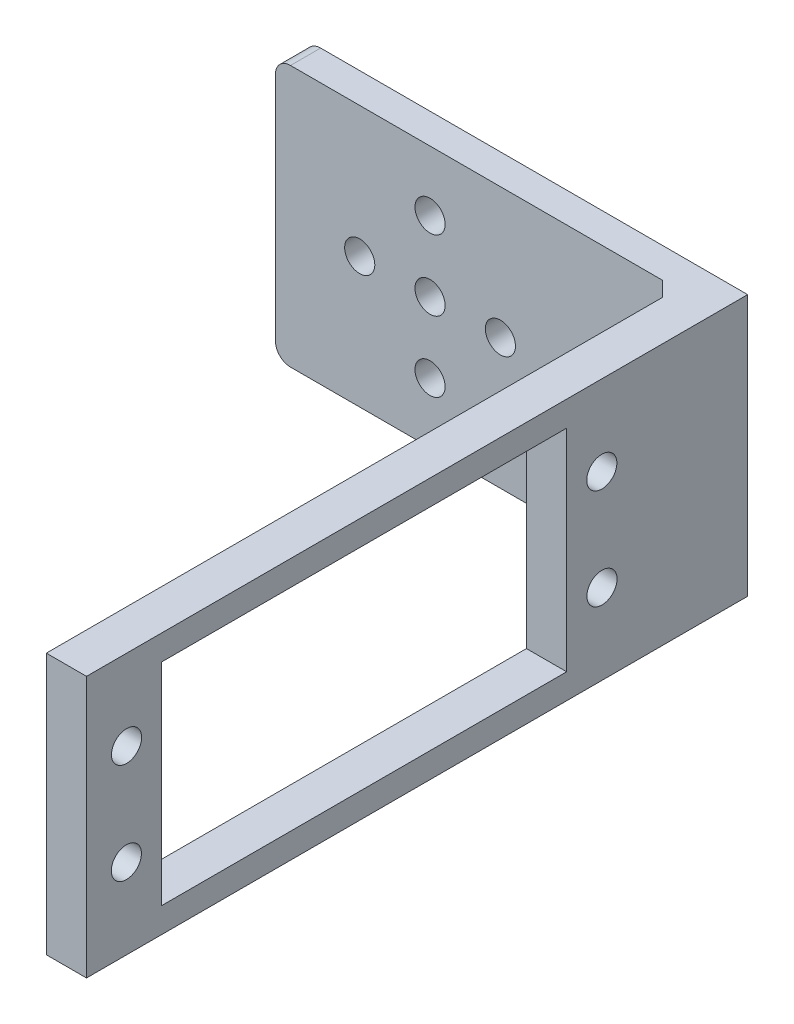
SolidWorks part; units mm, degrees
ref_plane "Alzado" through (0, 0, 0) normal (0, 0, 1) x (1, 0, 0)
ref_plane "Planta" through (0, 0, 0) normal (0, 1, 0) x (1, 0, 0)
ref_plane "Vista lateral" through (0, 0, 0) normal (1, 0, 0) x (0, 0, -1)
sketch "Croquis1" plane through (0, 0, 0) normal (0, 0, 1) x (1, 0, 0)
  line L0 (22, 0) -> (-6.61, 0) construction
  line L1 (-20.5, -13) -> (22, -13)
  line L2 (-22, -11.5) -> (-22, 11.5)
  line L3 (-20.5, 13) -> (22, 13)
  line L4 (22, -13) -> (22, 13)
  line L5 (-22, -13) -> (22, 13) construction
  line L6 (-22, 13) -> (22, -13) construction
  arc A0 (-20.5, -13) -> (-22, -11.5) centre (-20.5, -11.5) cw
  arc A1 (-22, 11.5) -> (-20.5, 13) centre (-20.5, 11.5) cw
  circle A2 centre (-6.61, 0) radius 1.5
  circle A3 centre (-13.61, 0) radius 1.5
  circle A4 centre (-6.61, 7) radius 1.5
  circle A5 centre (0.39, 0) radius 1.5
  circle A6 centre (-6.61, -7) radius 1.5
  point P0 (0, 0)
  dimension "D3" = 1.5
  dimension "D5" = 3
  dimension "D6" = 3
  dimension "D7" = 3
  dimension "D8" = 3
  dimension "D9" = 3
  dimension "D1" = 44
  dimension "D2" = 26
  dimension "D4" = 28.61
  dimension "D10" = 7
  dimension "D11" = 7
  dimension "D12" = 7
  dimension "D13" = 7
extrude "Saliente-Extruir1" add sketch "Croquis1" along normal blind 3
sketch "Croquis2" plane through (0, 0, 3) normal (0, 0, 1) x (1, 0, 0)
  line L0 (-20.5, -13) -> (22, -13) construction
  line L1 (22, 13) -> (18, 13)
  line L2 (22, 13) -> (22, -13)
  line L3 (22, -13) -> (18, -13)
  line L4 (18, 13) -> (18, -13)
  dimension "D1" = 4
extrude "Saliente-Extruir2" add sketch "Croquis2" along normal blind 62.8
sketch "Croquis3" plane through (0, -13, 0) normal (0, -1, 0) x (1, 0, 0)
  line L0 (18, 3) -> (18, 4.5)
  line L1 (18, 65.8) -> (18, 3) construction
  line L2 (18, 3) -> (16.5, 3)
  line L3 (-20.5, 3) -> (18, 3) construction
  line L4 (16.5, 3) -> (18, 4.5)
  dimension "D1" = 1.5
  dimension "D2" = 1.5
extrude "Saliente-Extruir3" add sketch "Croquis3" against normal blind 26
sketch "Croquis5" plane through (18, 0, 0) normal (-1, 0, 0) x (0, 0, 1)
  line L0 (18.0164, 0) -> (3, 0) construction
  line L2 (14.5164, 0) -> (14.5164, 5) construction
  line L3 (14.5164, 0) -> (18.0164, 0) construction
  line L4 (18.0164, -10.5) -> (18.0164, 10.5)
  line L5 (38.1664, -10.5) -> (38.1664, 10.5) construction
  line L6 (18.0164, 10.5) -> (58.3164, 10.5)
  line L7 (18.0164, 10.5) -> (18.0164, -10.5)
  line L8 (18.0164, -10.5) -> (58.3164, -10.5)
  line L9 (58.3164, 10.5) -> (58.3164, -10.5)
  line L10 (3, 13) -> (3, -13) construction
  circle A0 centre (14.5164, 5) radius 1.5
  circle A1 centre (14.5, -5) radius 1.5
  circle A2 centre (61.8164, 5) radius 1.5
  circle A3 centre (61.8328, -5) radius 1.5
  point P13 (18.0164, 0)
  dimension "D3" = 3
  dimension "D1" = 5
  dimension "D2" = 15.0164
  dimension "D4" = 3.5
  dimension "D5" = 21
  dimension "D6" = 40.3
extrude "Cortar-Extruir1" cut sketch "Croquis5" against normal blind 26 contours L9 L6 L4 L8 | A1 | A0 | A2 | A3
